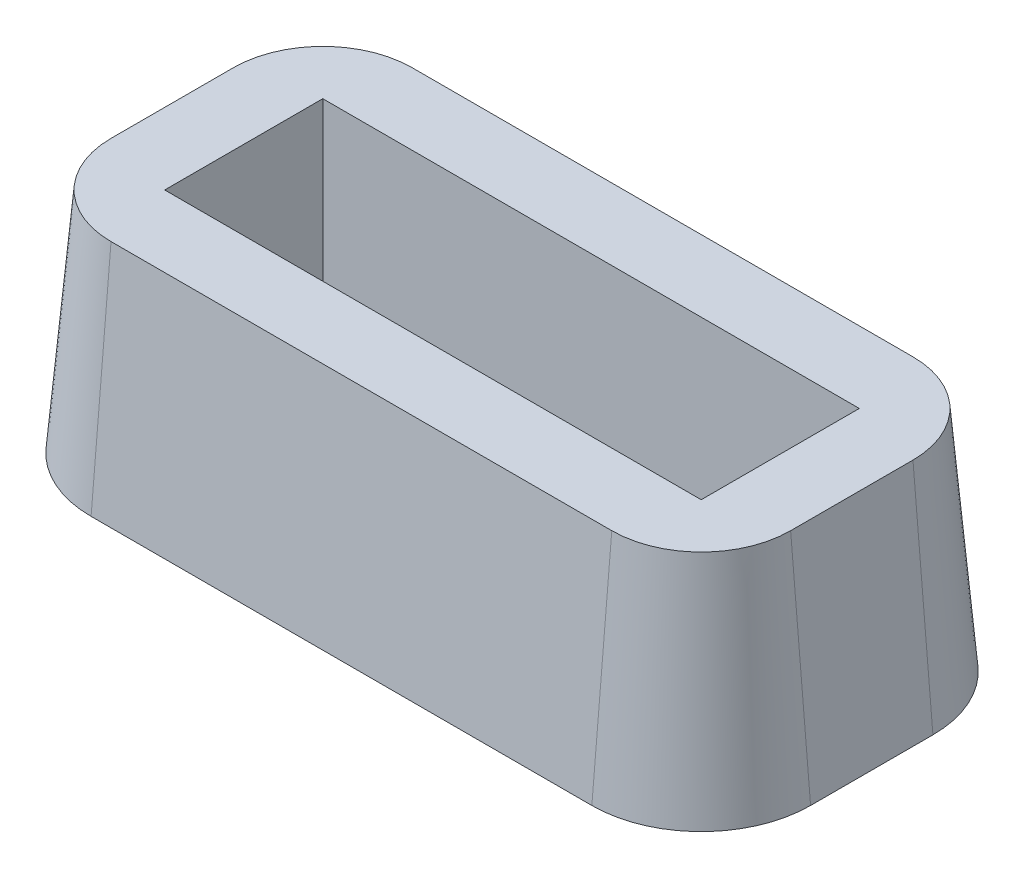
SolidWorks part; units mm, degrees
material "Copper"
ref_plane "Front Plane" through (0, 0, 0) normal (0, 0, 1) x (1, 0, 0)
ref_plane "Top Plane" through (0, 0, 0) normal (0, 1, 0) x (1, 0, 0)
ref_plane "Right Plane" through (0, 0, 0) normal (1, 0, 0) x (0, 0, -1)
sketch "Sketch1" plane through (0, 0, 0) normal (0, 1, 0) x (1, 0, 0)
  line L1 (15, -4.42) -> (-15, -4.42)
  line L2 (15, -4.42) -> (15, 4.42)
  line L3 (15, 4.42) -> (-15, 4.42)
  line L4 (-15, -4.42) -> (-15, 4.42)
  line L5 (15, -4.42) -> (-15, 4.42) construction
  line L6 (15, 4.42) -> (-15, -4.42) construction
  line L7 (14, -8.42) -> (-14, -8.42)
  line L8 (19, -3.42) -> (19, 3.42)
  line L9 (14, 8.42) -> (-14, 8.42)
  line L10 (-19, -3.42) -> (-19, 3.42)
  line L11 (19, -8.42) -> (-19, 8.42) construction
  line L12 (19, 8.42) -> (-19, -8.42) construction
  arc A0 (-14, -8.42) -> (-19, -3.42) centre (-14, -3.42) cw
  arc A1 (14, -8.42) -> (19, -3.42) centre (14, -3.42) ccw
  arc A2 (19, 3.42) -> (14, 8.42) centre (14, 3.42) ccw
  arc A3 (-14, 8.42) -> (-19, 3.42) centre (-14, 3.42) ccw
  point P0 (0, 0)
  point P5 (0, 0)
  dimension "D3" = 5
  dimension "D1" = 8.84
  dimension "D2" = 30
  dimension "D4" = 4
  dimension "D5" = 4
extrude "Boss-Extrude1" add sketch "Sketch1" along normal blind 12.75
draft "Draft1" type of draft neutral plane draft angle 5 faces to draft 8 face at (-17.0178, 6.375, 6.4378) face at (-19, 6.375, 0) face at (-17.0178, 6.375, -6.4378) face at (0, 6.375, -8.42) face at (17.0178, 6.375, -6.4378) face at (19, 6.375, 0) face at (17.0178, 6.375, 6.4378) face at (0, 6.375, 8.42) neutral plane through (-14, 12.75, 3.42) neutral plane normal (0, 1, 0) parameters "D1"=5
